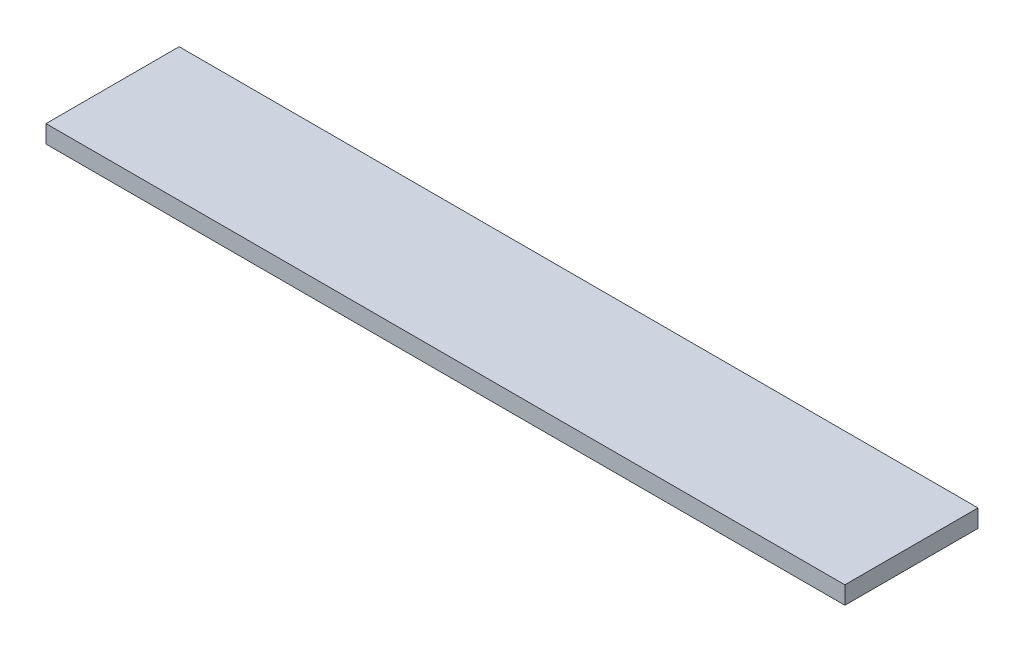
SolidWorks part; units mm, degrees
ref_plane "Front Plane" through (0, 0, 0) normal (0, 0, 1) x (1, 0, 0)
ref_plane "Top Plane" through (0, 0, 0) normal (0, 1, 0) x (1, 0, 0)
ref_plane "Right Plane" through (0, 0, 0) normal (1, 0, 0) x (0, 0, -1)
sketch "Sketch1" plane through (0, 0, 0) normal (1, 0, 0) x (0, 0, -1)
  line L1 (-7.5, 1) -> (7.5, 1)
  line L2 (-7.5, 1) -> (-7.5, -1)
  line L3 (-7.5, -1) -> (7.5, -1)
  line L4 (7.5, 1) -> (7.5, -1)
  line L5 (-7.5, 1) -> (7.5, -1) construction
  line L6 (-7.5, -1) -> (7.5, 1) construction
  point P0 (0, 0)
  dimension "D1" = 15
  dimension "D2" = 2
extrude "Boss-Extrude1" add sketch "Sketch1" along normal blind 90
